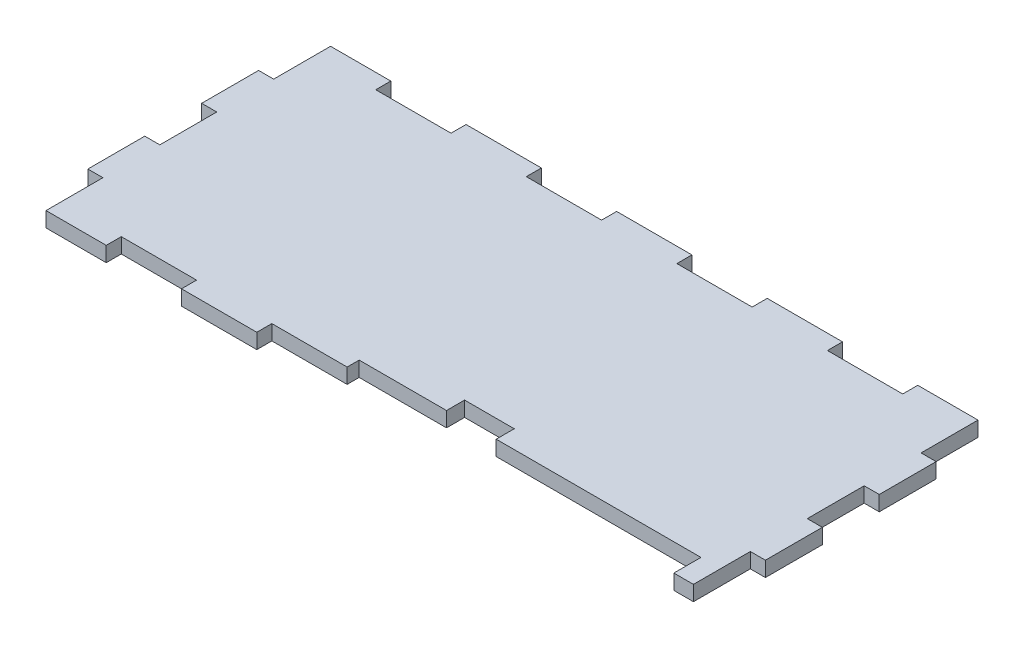
SolidWorks part; units mm, degrees
ref_plane "Front Plane" through (0, 0, 0) normal (0, 0, 1) x (1, 0, 0)
ref_plane "Top Plane" through (0, 0, 0) normal (0, 1, 0) x (1, 0, 0)
ref_plane "Right Plane" through (0, 0, 0) normal (1, 0, 0) x (0, 0, -1)
sketch "Sketch1" plane through (0, 0, 0) normal (0, 1, 0) x (1, 0, 0)
  line L1 (-57.15, 24.003) -> (57.15, 24.003)
  line L2 (-57.15, 24.003) -> (-57.15, -24.003)
  line L3 (-57.15, -24.003) -> (57.15, -24.003)
  line L4 (57.15, 24.003) -> (57.15, -24.003)
  line L5 (-57.15, 24.003) -> (57.15, -24.003) construction
  line L6 (-57.15, -24.003) -> (57.15, 24.003) construction
  point P0 (0, 0)
  dimension "D1" = 48.006
  dimension "D2" = 114.3
extrude "Boss-Extrude1" add sketch "Sketch1" along normal blind 2.54
sketch "Sketch2" plane through (0, 2.54, 0) normal (0, 1, 0) x (1, 0, 0)
  line L0 (57.15, -14.4018) -> (54.61, -14.4018)
  line L1 (57.15, -24.003) -> (57.15, 24.003) construction
  line L2 (54.61, -14.4018) -> (54.61, -24.003)
  line L3 (54.61, -24.003) -> (44.45, -24.003)
  line L4 (44.45, -24.003) -> (44.45, -21.463)
  line L5 (44.45, -21.463) -> (31.75, -21.463)
  line L6 (31.75, -21.463) -> (31.75, -24.003)
  line L7 (-57.15, -24.003) -> (57.15, -24.003) construction
  line L8 (31.75, -24.003) -> (19.05, -24.003)
  line L9 (19.05, -24.003) -> (19.05, -21.463)
  line L10 (19.05, -21.463) -> (6.35, -21.463)
  line L11 (6.35, -21.463) -> (6.35, -24.003)
  line L12 (6.35, -24.003) -> (-6.35, -24.003)
  line L13 (-6.35, -24.003) -> (-6.35, -21.463)
  line L14 (-6.35, -21.463) -> (-19.05, -21.463)
  line L15 (-19.05, -21.463) -> (-19.05, -24.003)
  line L16 (-19.05, -24.003) -> (-31.75, -24.003)
  line L17 (-31.75, -24.003) -> (-31.75, -21.463)
  line L18 (-31.75, -21.463) -> (-44.45, -21.463)
  line L19 (-44.45, -21.463) -> (-44.45, -24.003)
  line L20 (-44.45, -24.003) -> (-54.61, -24.003)
  line L21 (-54.61, -24.003) -> (-54.61, -14.4018)
  line L22 (-54.61, -14.4018) -> (-57.15, -14.4018)
  line L23 (-57.15, 24.003) -> (-57.15, -24.003) construction
  line L24 (57.15, -14.4018) -> (57.15, -4.8006)
  line L25 (57.15, -4.8006) -> (54.61, -4.8006)
  line L26 (54.61, -4.8006) -> (54.61, 4.8006)
  line L27 (54.61, 4.8006) -> (57.15, 4.8006)
  line L28 (57.15, 4.8006) -> (57.15, 14.4018)
  line L29 (57.15, 14.4018) -> (54.61, 14.4018)
  line L30 (54.61, 14.4018) -> (54.61, 24.003)
  line L31 (-57.15, -14.4018) -> (-57.15, -4.8006)
  line L32 (-57.15, -4.8006) -> (-54.61, -4.8006)
  line L33 (-54.61, -4.8006) -> (-54.61, 4.8006)
  line L34 (-54.61, 4.8006) -> (-57.15, 4.8006)
  line L35 (-57.15, 4.8006) -> (-57.15, 14.4018)
  line L36 (-57.15, 14.4018) -> (-54.61, 14.4018)
  line L37 (-54.61, 14.4018) -> (-54.61, 24.003)
  line L38 (57.15, 24.003) -> (-57.15, 24.003) construction
  line L39 (54.61, 24.003) -> (44.45, 24.003)
  line L40 (44.45, 24.003) -> (44.45, 21.463)
  line L41 (44.45, 21.463) -> (31.75, 21.463)
  line L42 (31.75, 21.463) -> (31.75, 24.003)
  line L43 (31.75, 24.003) -> (19.05, 24.003)
  line L44 (19.05, 24.003) -> (19.05, 21.463)
  line L45 (19.05, 21.463) -> (6.35, 21.463)
  line L46 (6.35, 21.463) -> (6.35, 24.003)
  line L47 (6.35, 24.003) -> (-6.35, 24.003)
  line L48 (-6.35, 24.003) -> (-6.35, 21.463)
  line L49 (-6.35, 21.463) -> (-19.05, 21.463)
  line L50 (-19.05, 21.463) -> (-19.05, 24.003)
  line L51 (-19.05, 24.003) -> (-31.75, 24.003)
  line L52 (-31.75, 24.003) -> (-31.75, 21.463)
  line L53 (-31.75, 21.463) -> (-44.45, 21.463)
  line L54 (-44.45, 21.463) -> (-44.45, 24.003)
  line L55 (-44.45, 24.003) -> (-54.61, 24.003)
  line M11 (57.15, -24.003) -> (57.15, 24.003)
  line M12 (57.15, 24.003) -> (-57.15, 24.003)
  line M13 (-57.15, 24.003) -> (-57.15, -24.003)
  line M14 (-57.15, -24.003) -> (57.15, -24.003)
  dimension "D1" = 9.6012
  dimension "D2" = 2.54
  dimension "D3" = 2.54
  dimension "D4" = 12.7
  dimension "D5" = 9.6012
  dimension "D6" = 2.54
  dimension "D7" = 2.54
  dimension "D8" = 12.7
  dimension "D9" = 2.54
extrude "Cut-Extrude2" cut sketch "Sketch2" against normal up to next contours L36 L37 M12 M13 | L54 L53 L52 M12 | L50 L49 L48 M12 | L46 L45 L44 M12 | L42 L41 L40 M12 | L30 L29 M11 M12 | L27 L26 L25 M11 | L0 L2 M14 M11 | L5 L6 L4 M14 | L10 L11 L9 M14 | L14 L15 L13 M14 | L18 L19 L17 M14 | L21 L22 M13 M14 | L33 L34 L32 M13
sketch "Sketch5" plane through (0, 2.54, 0) normal (0, 1, 0) x (1, 0, 0)
  line L0 (16.764, -19.431) -> (51.308, -19.431)
  line L1 (-6.35, -19.431) -> (8.382, -19.431)
  line L2 (-6.35, -19.431) -> (-6.35, -24.003)
  line L3 (-6.35, -24.003) -> (51.308, -24.003)
  line L4 (51.308, -19.431) -> (51.308, -24.003)
  line L6 (-6.35, -24.003) -> (-6.35, -21.463) construction
  line L8 (57.15, -14.4018) -> (57.15, -4.8006) construction
  line L9 (8.382, -16.383) -> (16.764, -16.383)
  line L10 (8.382, -16.383) -> (8.382, -19.431)
  line L12 (16.764, -16.383) -> (16.764, -19.431)
  line L13 (-6.35, -24.003) -> (6.35, -24.003) construction
  dimension "D1" = 4.572
  dimension "D2" = 5.842
  dimension "D3" = 8.382
  dimension "D4" = 42.926
  dimension "D5" = 3.048
extrude "Cut-Extrude3" cut sketch "Sketch5" against normal blind 2.54
